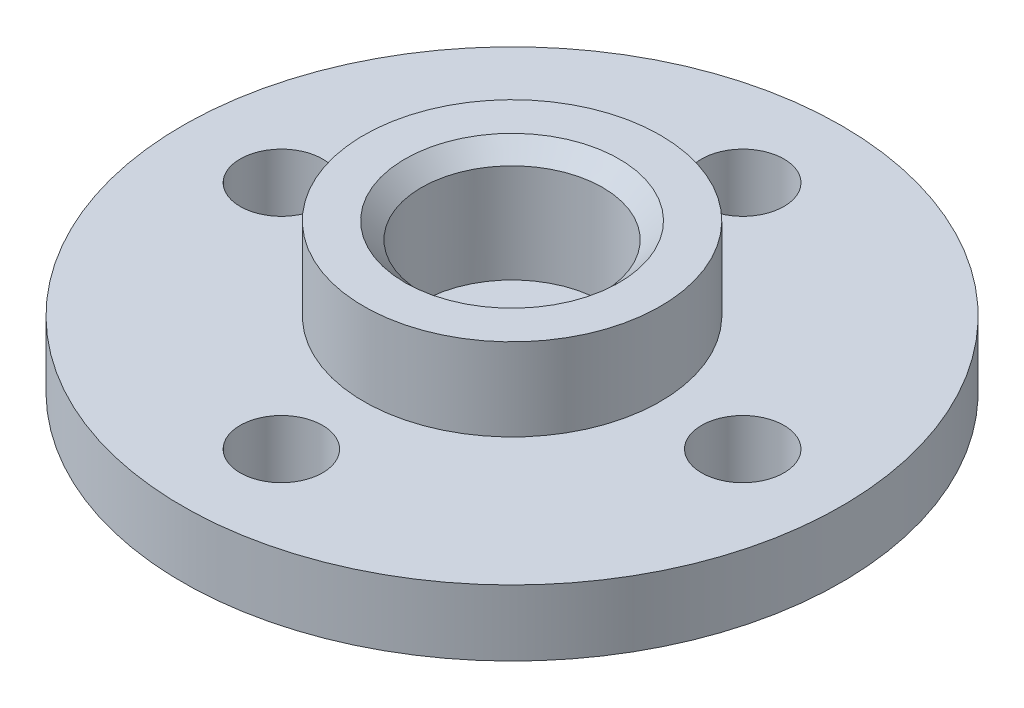
SolidWorks part; units mm, degrees
ref_plane "前视基准面" through (0, 0, 0) normal (0, 0, 1) x (1, 0, 0)
ref_plane "上视基准面" through (0, 0, 0) normal (0, 1, 0) x (1, 0, 0)
ref_plane "右视基准面" through (0, 0, 0) normal (1, 0, 0) x (0, 0, -1)
sketch "草图1" plane through (0, 0, 0) normal (1, 0, 0) x (0, 0, -1)
  line L0 (2.75, 0) -> (10, 0)
  line L1 (10, 0) -> (10, 2)
  line L2 (10, 2) -> (4.5, 2)
  line L3 (4.5, 2) -> (4.5, 4.5)
  line L4 (4.5, 4.5) -> (2.75, 4.5)
  line L6 (2.75, 4.5) -> (2.75, 1)
  line L7 (2.75, 1) -> (1, 1)
  line L8 (1, 1) -> (1, 0)
  line L9 (1, 0) -> (2.75, 0)
  line L10 (0, 0) -> (0, 12.2653) construction
  dimension "D1" = 4.5
  dimension "D2" = 5.5
  dimension "D3" = 2
  dimension "D4" = 4.5
  dimension "D5" = 10
  dimension "D6" = 1
  dimension "D7" = 2
revolve "旋转1" add sketch "草图1" angle 360 about L10
hole_wizard "M3 螺纹孔的螺纹孔钻头1" positions "草图2" profile "草图4" hole size "M3" standard "GB" end condition through all
sketch "草图2" plane through (0, 2, 0) normal (0, 1, 0) x (1, 0, 0)
  circle A0 centre (0, 0) radius 7
  point P5 (0, 7)
  point P7 (-7, 0)
  point P9 (7, 0)
  point P11 (0, -7)
  dimension "D1" = 14
sketch "草图4" plane through (0, 2, 7) normal (1, 0, 0) x (0, 0, 1)
  line L0 (0, 0) -> (0, 2)
  line L1 (0, 2) -> (1.25, 2)
  line L2 (1.25, 2) -> (1.25, 0)
  line L5 (1.25, 0) -> (0, 0)
  line L11 (0, -6.35) -> (0, 107.95) construction
  dimension "通孔孔直径" = 2.5
  dimension "通孔孔深度" = 2
chamfer "倒角1" distance 0.5 angle 45 1 edges at (0, 4.5, -2.75)
